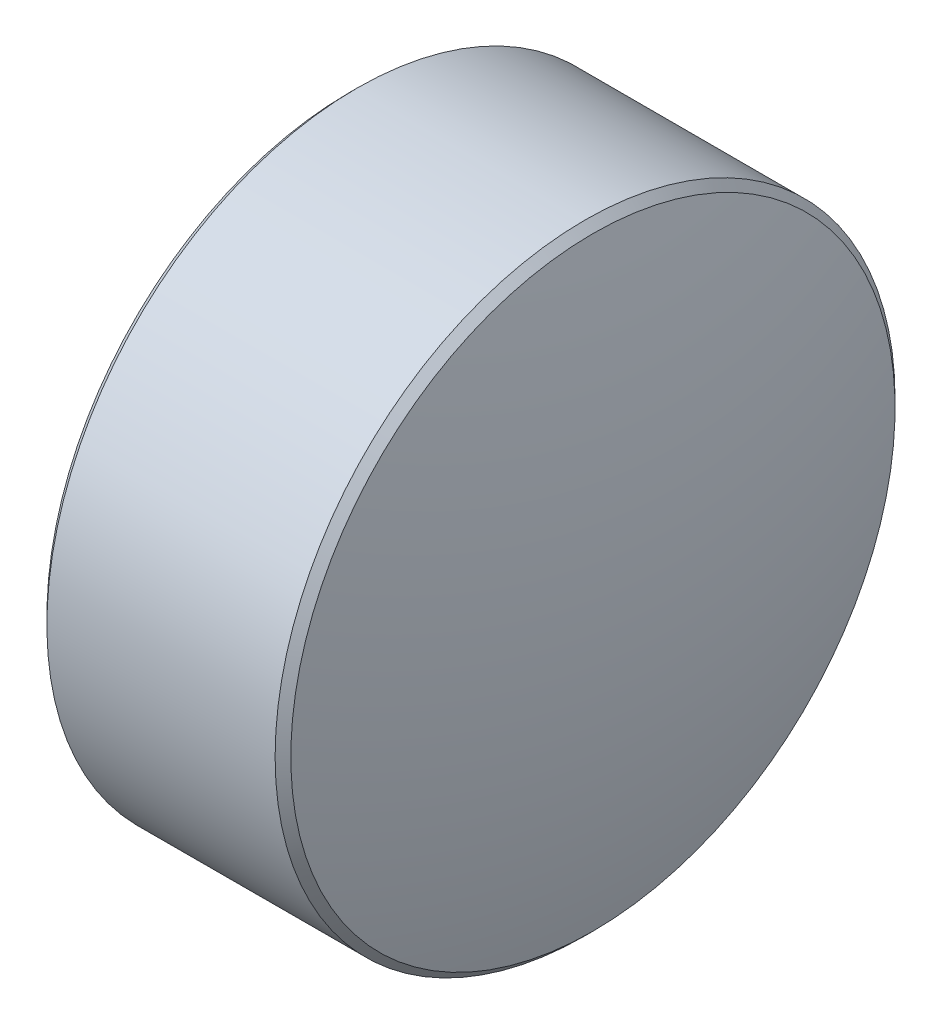
SolidWorks part; units mm, degrees
material "Glass"
ref_plane "Front Plane" through (0, 0, 0) normal (0, 0, 1) x (1, 0, 0)
ref_plane "Top Plane" through (0, 0, 0) normal (0, 1, 0) x (1, 0, 0)
ref_plane "Right Plane" through (0, 0, 0) normal (1, 0, 0) x (0, 0, -1)
sketch "Sketch1" plane through (0, 0, 0) normal (0, 0, 1) x (1, 0, 0)
  line L1 (4.25, 11) -> (-4.25, 11)
  line L3 (4.25, -11) -> (-4.25, -11)
  line L4 (20.6854, 0) -> (-20.6854, 0) construction
  arc A0 (-4.25, -11) -> (-4.25, 11) centre (34.2078, 0) cw
  arc A1 (4.25, -11) -> (4.25, 11) centre (-34.2078, 0) ccw
  point P1 (5.7922, 0)
  point P7 (0, 0)
  point P9 (-5.7922, 0)
  point P14 (0, 0)
  dimension "D3" = 40
  dimension "D4" = 40
  dimension "b" = 8.5
  dimension "D2" = 22
  dimension "D1" = 4.25
revolve "Revolve1" add sketch "Sketch1" angle 360 about L4
chamfer "Chamfer2" distance 0.2 angle 45 2 edges at (-4.25, 11, 0) (4.25, 11, 0)
ref_plane "Plane1" through (-4.3296, 0, 0) normal (1, 0, 0) x (0, 0, -1)
equation "\"D1@Sketch1\"= \"b\" / 2"
